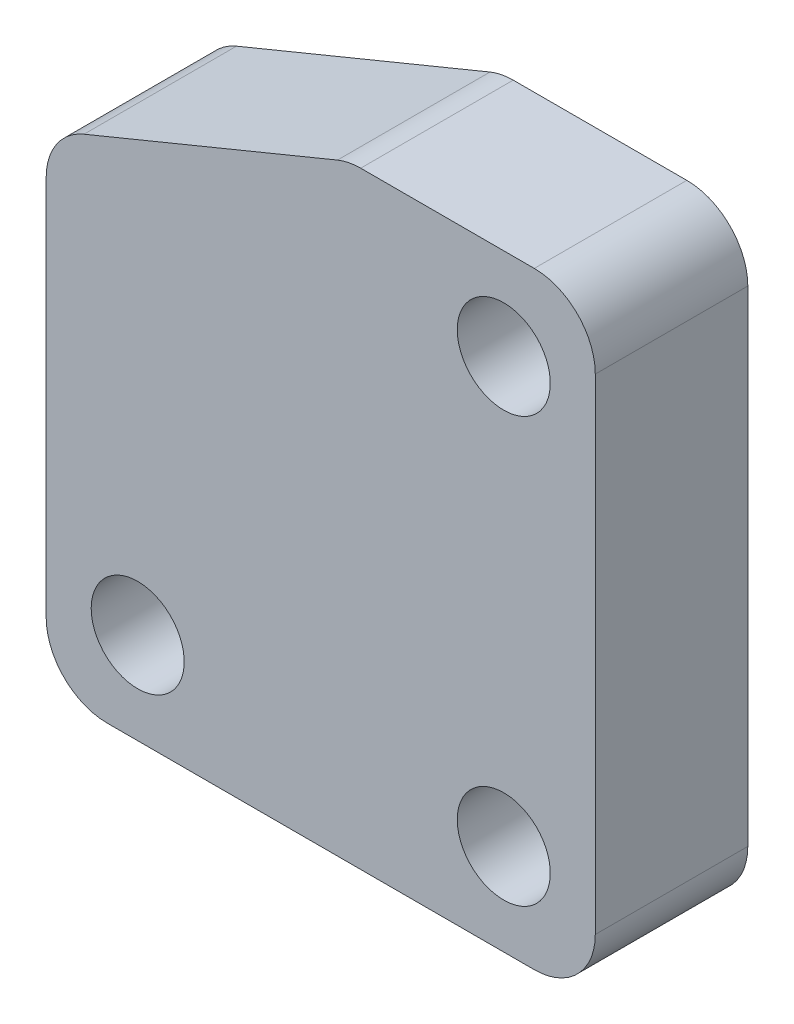
SolidWorks part; units mm, degrees
material "ABS"
ref_plane "前视基准面" through (0, 0, 0) normal (0, 0, 1) x (1, 0, 0)
ref_plane "上视基准面" through (0, 0, 0) normal (0, 1, 0) x (1, 0, 0)
ref_plane "右视基准面" through (0, 0, 0) normal (1, 0, 0) x (0, 0, -1)
other "Configuration Table"
sketch "草图1" plane through (0, 0, 0) normal (0, 0, 1) x (1, 0, 0)
  line L1 (-10, -10) -> (10, -10)
  line L2 (-10, -10) -> (-10, 10)
  line L3 (-10, 10) -> (10, 10)
  line L4 (10, -10) -> (10, 10)
  line L5 (-10, -10) -> (10, 10) construction
  line L6 (-10, 10) -> (10, -10) construction
  point P0 (0, 0)
  dimension "D1" = 20
extrude "凸台-拉伸1" add sketch "草图1" along normal blind 5
chamfer "倒角1" distance 15 angle 45 1 edges at (10, 10, 2.5)
fillet "圆角1" radius 5 1 edges at (-10, -10, 2.5)
sketch "草图3" plane through (0, 0, 0) normal (0, 0, -1) x (-1, 0, 0)
  circle A0 centre (-33.46, 2.1384) radius 1.25 construction
  circle A1 centre (-33.46, -11.7704) radius 1.25 construction
  circle A2 centre (-45.46, -11.7704) radius 1.25 construction
  circle A3 centre (-45.46, 2.1384) radius 1.25 construction
  circle A4 centre (-33.46, 2.1384) radius 1.25
  circle A5 centre (-33.46, -11.7704) radius 1.25
  circle A6 centre (-45.46, -11.7704) radius 1.25
  circle A7 centre (-45.46, 2.1384) radius 1.25
sketch "草图2" plane through (0, 0, 0) normal (0, 0, -1) x (-1, 0, 0)
  line L0 (-6, -1) -> (-30.46, -1)
  line L1 (5, 10) -> (-10, -5) construction
  line L2 (-30.46, -1) -> (-30.46, 5.1384)
  line L3 (-30.46, 5.1384) -> (-48.46, 5.1384)
  line L4 (-48.46, 5.1384) -> (-48.46, -14.7704)
  line L5 (-10, -10) -> (-30.46, -14.7704)
  line L6 (-30.46, -14.7704) -> (-48.46, -14.7704)
  line L7 (5, -10) -> (-10, -10) construction
  line L8 (-6, -1) -> (-10, -10)
  circle A0 centre (-33.46, -11.7704) radius 1.25 construction
  circle A1 centre (-33.46, 2.1384) radius 1.25 construction
  circle A2 centre (-45.46, -11.7704) radius 1.25 construction
  circle A3 centre (-45.46, 2.1384) radius 1.25 construction
  circle A4 centre (-33.46, 2.1384) radius 1.25 construction
  circle A5 centre (-33.46, -11.7704) radius 1.25 construction
  circle A6 centre (-45.46, -11.7704) radius 1.25 construction
  circle A7 centre (-45.46, 2.1384) radius 1.25 construction
  circle A8 centre (-45.46, 2.1384) radius 1.525
  circle A9 centre (-45.46, -11.7704) radius 1.525
  circle A10 centre (-33.46, -11.7704) radius 1.525
  circle A11 centre (-33.46, 2.1384) radius 1.525
  dimension "D7" = 3.05
  dimension "D1" = 3
  dimension "D2" = 3
  dimension "D3" = 3
  dimension "D4" = 9
  dimension "D5" = 3
  dimension "D6" = 3
extrude "凸台-拉伸2" add sketch "草图2" against normal up to surface (5 mm away) up to face at (-1.8393, -1.8393, 5)
chamfer "倒角2" distance 5 angle 45 1 edges at (30.46, -1, 2.5)
chamfer "倒角3" distance 1 angle 45 1 edges at (30.46, 5.1384, 2.5)
fillet "圆角2" radius 2 2 edges at (31.46, 5.1384, 2.5) (30.46, 4.1384, 2.5)
sketch "草图4" plane through (0, 0, 0) normal (0, 0, -1) x (-1, 0, 0)
  line L0 (-25.46, -1) -> (-40.3742, 5.1384)
  line L1 (-32.2884, 5.1384) -> (-48.46, 5.1384) construction
  line L2 (-40.3742, 5.1384) -> (-25.46, 5.1384)
  line L3 (-25.46, 5.1384) -> (-25.46, -1)
extrude "切除-拉伸1" cut sketch "草图4" against normal up to surface (5 mm away) up to face at (18.7269, -1.0061, 5)
sketch "草图5" plane through (0, 0, 0) normal (0, 0, -1) x (-1, 0, 0)
  line L0 (-34.8097, 2.8482) -> (-32.0016, 1.6924)
  line L1 (-32.0016, 1.6924) -> (-25.46, -1) construction
  arc A0 (-34.8097, 2.8482) -> (-32.0016, 1.6924) centre (-33.46, 2.1384) ccw construction
  arc A2 (-34.8097, 2.8482) -> (-32.0016, 1.6924) centre (-33.46, 2.1384) ccw
extrude "凸台-拉伸3" add sketch "草图5" against normal up to surface (5 mm away) up to face at (43.935, -11.7704, 5)
sketch "草图6" plane through (0, 0, 0) normal (0, 0, -1) x (-1, 0, 0)
  line L0 (-30.46, -14.7704) -> (-30.46, 11.2296)
  line L1 (-30.46, 11.2296) -> (1.54, 11.2296)
  line L2 (1.54, 11.2296) -> (1.54, -14.7704)
  line L3 (1.54, -14.7704) -> (-30.46, -14.7704)
  dimension "D1" = 26
  dimension "D2" = 32
extrude "切除-拉伸2" cut sketch "草图6" against normal up to surface (5 mm away) up to face at (43.935, -11.7704, 5)
sketch "草图7" [suppressed] plane through (0, 0, 3) normal (0, 0, 1) x (1, 0, 0)
  circle A0 centre (7.3, -6) radius 1.25 construction
  circle A1 centre (-4.7, 6) radius 1.25 construction
  circle A2 centre (7.3, -6) radius 1.25 construction
  circle A3 centre (-4.7, 6) radius 1.25 construction
  circle A4 centre (-4.7, 6) radius 1.525
  circle A5 centre (7.3, -6) radius 1.525
  dimension "D1" = 3.05
extrude "切除-拉伸3" [suppressed] cut sketch "草图7" against normal up to surface (3 mm away)
fillet "圆角3" [suppressed] radius 2
fillet "圆角4" radius 2 5 edges at (48.46, 5.1384, 2.5) (48.46, -14.7704, 2.5) (30.46, -14.7704, 2.5) (40.3742, 5.1384, 2.5) (30.46, 1.0579, 2.5)
delete or keep bodies "实体-删除/保留 1" type delete bodies bodies 114
